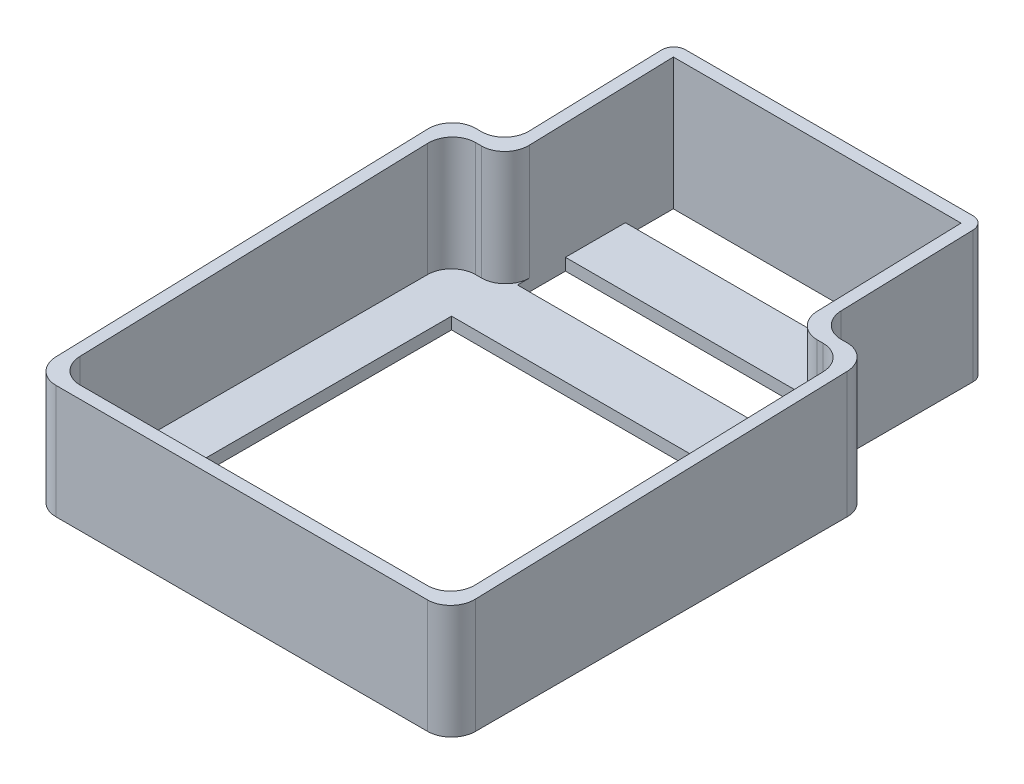
SolidWorks part; units mm, degrees
other "Markup1"
sketch "Sketch5" plane through (35, 0, 49) normal (0.0121, -0.9994, 0.0328) x (-0.9747, -0.0044, 0.2233)
ref_plane "Front Plane" through (0, 0, 0) normal (0, 0, 1) x (1, 0, 0)
ref_plane "Top Plane" through (0, 0, 0) normal (0, 1, 0) x (1, 0, 0)
ref_plane "Right Plane" through (0, 0, 0) normal (1, 0, 0) x (0, 0, -1)
sketch "Sketch1" plane through (0, 0, 0) normal (0, 1, 0) x (1, 0, 0)
  line L0 (0, 0) -> (0, -46.427) construction
  line L1 (-35, 49) -> (35, 49)
  line L2 (-35, 49) -> (-35, -49)
  line L3 (-35, -49) -> (35, -49)
  line L4 (35, 49) -> (35, -49)
  line L5 (-35, 49) -> (35, -49) construction
  line L6 (-35, -49) -> (35, 49) construction
  line L7 (0, 0) -> (0, 63.2697) construction
  line L8 (-24, 29) -> (-24, 21)
  line L9 (-25, 11) -> (25, 11)
  line L10 (-25, 11) -> (-25, -39)
  line L11 (-25, -39) -> (25, -39)
  line L12 (25, 11) -> (25, -39)
  line L13 (-25, 11) -> (25, -39) construction
  line L14 (-25, -39) -> (25, 11) construction
  line L15 (-24, 47) -> (24, 47)
  line L16 (-24, 47) -> (-24, 39)
  line L17 (-24, 21) -> (24, 21)
  line L18 (24, 47) -> (24, 39)
  line L19 (-24, 47) -> (24, 21) construction
  line L20 (-24, 21) -> (24, 47) construction
  line L21 (-24, 39) -> (24, 39)
  line L23 (-24, 29) -> (24, 29)
  line L25 (-24, 39) -> (24, 29) construction
  line L26 (-24, 29) -> (24, 39) construction
  line L27 (24, 29) -> (24, 21)
  line L28 (-35, 21) -> (-26, 21)
  line L29 (-26, 21) -> (-26, 49)
  line L30 (-26, 49) -> (26, 49)
  line L31 (26, 49) -> (26, 21)
  line L32 (26, 21) -> (35, 21)
  point P0 (0, 0)
  point P8 (0, -14)
  point P14 (0, 34)
  point P19 (0, 34)
  dimension "D1" = 70
  dimension "D2" = 50
  dimension "D3" = 50
  dimension "D4" = 10
  dimension "D5" = 10
  dimension "D6" = 48
  dimension "D7" = 26
  dimension "D8" = 10
  dimension "D9" = 2
  dimension "D10" = 2
  dimension "D11" = 2
extrude "Boss-Extrude1" add sketch "Sketch1" along normal blind 2 contours L32 L31 L1 L29 L28 L2 L3 L4 L21 L16 L15 L18 L9 L12 L11 L10 L23 L27 L17 L8
fillet "Fillet1" radius 4 6 edges at (35, 1, 49) (-35, 1, 49) (35, 1, -21) (26, 1, -21) (-35, 1, -21) (-26, 1, -21)
fillet "Fillet2" radius 2 2 edges at (26, 1, -49) (-26, 1, -49)
sketch "Sketch4" plane through (0, 2, 0) normal (0, 1, 0) x (1, 0, 0)
  line L0 (-31, -49) -> (31, -49)
  line L1 (35, -45) -> (35, 17)
  line L2 (31, 21) -> (30, 21)
  line L3 (26, 25) -> (26, 47)
  line L4 (24, 49) -> (-24, 49)
  line L5 (-26, 47) -> (-26, 25)
  line L6 (-30, 21) -> (-31, 21)
  line L7 (-35, 17) -> (-35, -45)
  line L8 (-24, 49) -> (24, 49) construction
  line L9 (-26, 25) -> (-26, 47) construction
  line L10 (26, 47) -> (26, 25) construction
  line L11 (30, 21) -> (31, 21) construction
  line L12 (35, 17) -> (35, -45) construction
  line L13 (-31, -49) -> (31, -49) construction
  line L14 (-35, 17) -> (-35, -45) construction
  line L15 (-31, 21) -> (-30, 21) construction
  line L16 (-29, 19) -> (-28, 19)
  line L17 (-24, 23) -> (-24, 47)
  line L18 (-24, 47) -> (24, 47) construction
  line L19 (-24, 47) -> (24, 47)
  line L20 (24, 47) -> (24, 23)
  line L21 (28, 19) -> (29, 19)
  line L22 (33, 15) -> (33, -43)
  line L23 (29, -47) -> (-29, -47)
  line L24 (-33, -43) -> (-33, 15)
  line L25 (-24, 29) -> (-24, 21) construction
  arc A0 (31, -49) -> (35, -45) centre (31, -45) ccw
  arc A1 (33, -43) -> (29, -47) centre (29, -43) cw
  arc A2 (35, 17) -> (31, 21) centre (31, 17) ccw
  arc A3 (30, 21) -> (26, 25) centre (30, 25) cw
  arc A4 (24, 23) -> (28, 19) centre (28, 23) ccw
  arc A5 (29, 19) -> (33, 15) centre (29, 15) cw
  arc A6 (-26, 25) -> (-30, 21) centre (-30, 25) cw
  arc A7 (-28, 19) -> (-24, 23) centre (-28, 23) ccw
  arc A8 (-29, 19) -> (-33, 15) centre (-29, 15) ccw
  arc A9 (-31, 21) -> (-35, 17) centre (-31, 17) ccw
  arc A10 (-29, -47) -> (-33, -43) centre (-29, -43) cw
  arc A11 (-31, -49) -> (-35, -45) centre (-31, -45) cw
  arc A12 (26, 47) -> (24, 49) centre (24, 47) ccw
  arc A13 (-24, 49) -> (-26, 47) centre (-24, 47) ccw
  dimension "D6" = 4
  dimension "D7" = 2
  dimension "D1" = 2
  dimension "D2" = 2
  dimension "D3" = 2
  dimension "D4" = 2
  dimension "D5" = 2
extrude "Boss-Extrude2" add sketch "Sketch4" along normal blind 20
sketch "Sketch6" plane through (0, 0, 0) normal (1, 0, 0) x (0, 0, -1)
  line L4 (-49, 22) -> (-49, 19)
  line L5 (-49, 0) -> (-49, 22) construction
  line L6 (-49, 19) -> (49, 22)
  line L7 (49, 22) -> (-49, 22)
  dimension "D1" = 3
extrude "Cut-Extrude1" cut sketch "Sketch6" against normal through all both and the other way through all contours L7 L4 L6
